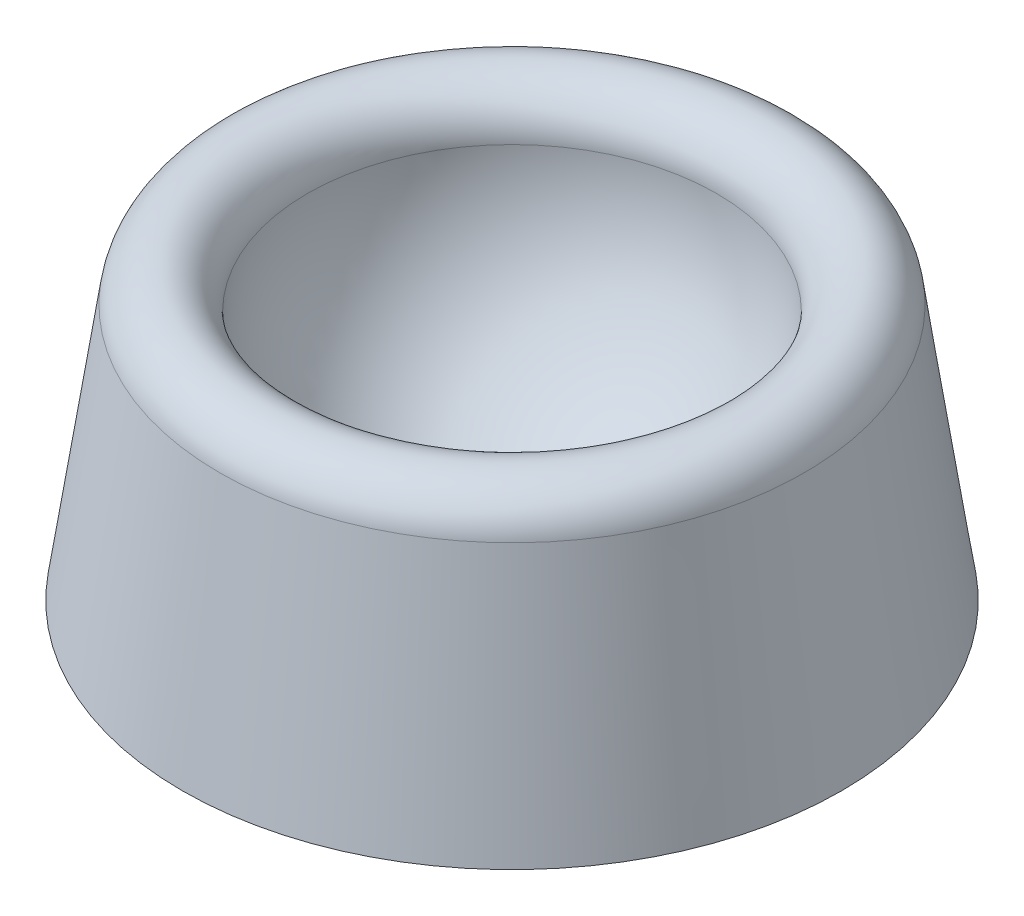
SolidWorks part; units mm, degrees
material "AA380.0-F matrice"
ref_plane "Plan de face" through (0, 0, 0) normal (0, 0, 1) x (1, 0, 0)
ref_plane "Plan de dessus" through (0, 0, 0) normal (0, 1, 0) x (1, 0, 0)
ref_plane "Plan de droite" through (0, 0, 0) normal (1, 0, 0) x (0, 0, -1)
sketch "Esquisse1" plane through (0, 0, 0) normal (0, 0, 1) x (1, 0, 0)
  line L0 (0, 18.0177) -> (0, -18.121) construction
  line L1 (-38.7295, 0) -> (36.4389, 0) construction
  line L2 (0, -10) -> (0, -9)
  line L3 (-13.5, -11) -> (-11.8575, 0.1362)
  line L4 (-13.5, -11) -> (-14.5, -11)
  line L5 (-14.5, -11) -> (-12.8471, 0.2804)
  line L6 (-10.3723, 0.502) -> (-10.3723, -0.3925) construction
  arc A0 (-9, 0) -> (0, -9) centre (0, 0) ccw
  arc A1 (-10, 0) -> (0, -10) centre (0, 0) ccw
  arc A2 (-10, 0) -> (-11.8575, 0.1362) centre (-10.9338, 0) ccw
  arc A3 (-9, 0) -> (-12.8471, 0.2804) centre (-10.9338, 0) ccw
  dimension "D1" = 9
  dimension "D2" = 10
  dimension "D3" = 14.5
  dimension "D4" = 11
  dimension "D5" = 8.39
  dimension "D6" = 1
revolve "Révolution1" add sketch "Esquisse1" angle 360 about L0
